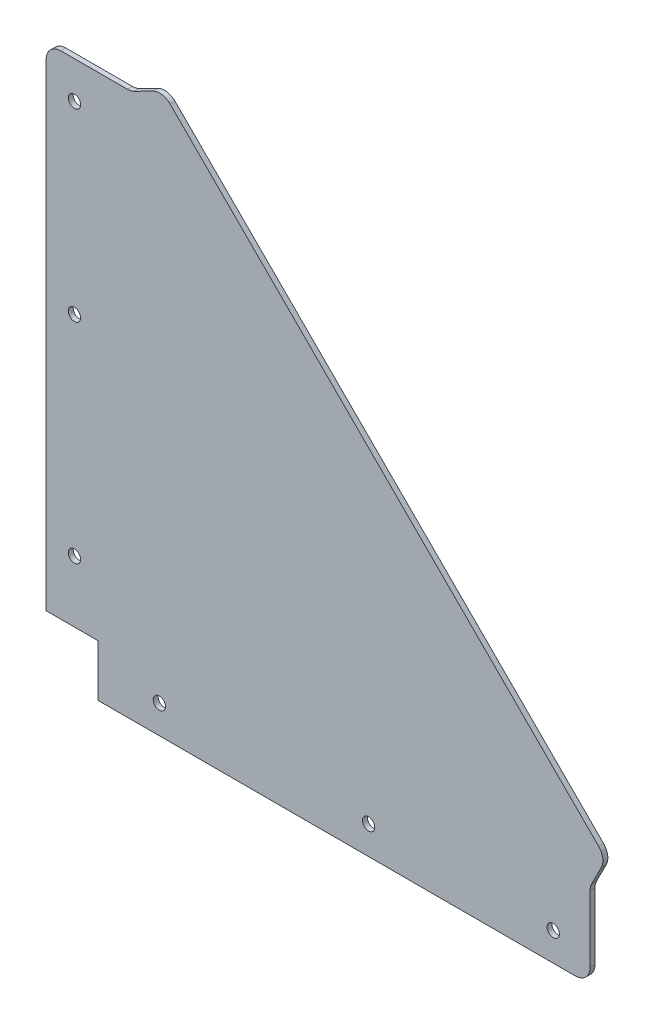
SolidWorks part; units mm, degrees
ref_plane "前基準面" through (0, 0, 0) normal (0, 0, 1) x (1, 0, 0)
ref_plane "上基準面" through (0, 0, 0) normal (0, 1, 0) x (1, 0, 0)
ref_plane "右基準面" through (0, 0, 0) normal (1, 0, 0) x (0, 0, -1)
ref_plane "平面1"
sketch "草圖1" plane through (0, 0, 0) normal (0, 0, 1) x (1, 0, 0)
  line L0 (21, 21) -> (0, 21)
  line L1 (0, 21) -> (0, 221)
  line L2 (0, 221) -> (34.5, 221)
  line L3 (34.5, 221) -> (47.3011, 227.5225)
  line L4 (47.3011, 227.5225) -> (227.5225, 47.3011)
  line L5 (227.5225, 47.3011) -> (222.5286, 37.5)
  line L6 (222.5286, 37.5) -> (221, 34.5)
  line L7 (221, 34.5) -> (221, 21)
  line L8 (221, 21) -> (221, 0)
  line L9 (221, 0) -> (21, 0)
  line L10 (21, 0) -> (21, 21)
  circle A0 centre (206, 11.5) radius 2.5
  circle A1 centre (131, 11.5) radius 2.5
  circle A2 centre (46, 11.5) radius 2.5
  circle A3 centre (11.5, 206) radius 2.5
  circle A4 centre (11.5, 131) radius 2.5
  circle A5 centre (11.5, 46) radius 2.5
  dimension "D12" = 5
  dimension "D14" = 5
  dimension "D15" = 5
  dimension "D21" = 5
  dimension "D22" = 5
  dimension "D23" = 5
  dimension "D1" = 21
  dimension "D2" = 21
  dimension "D3" = 200
  dimension "D4" = 200
  dimension "D5" = 21
  dimension "D6" = 13.5
  dimension "D7" = 153
  dimension "D8" = 16.5707
  dimension "D9" = 11
  dimension "D10" = 45
  dimension "D11" = 153
  dimension "D13" = 11.5
  dimension "D16" = 206
  dimension "D17" = 11.5
  dimension "D18" = 15
  dimension "D19" = 75
  dimension "D20" = 85
  dimension "D24" = 11.5
  dimension "D25" = 11.5
  dimension "D26" = 11.5
  dimension "D27" = 90
  dimension "D28" = 75
  dimension "D29" = 85
extrude "擠出1" add sketch "草圖1" along normal blind 2 contours L10 L9 L8 L7 L6 L5 L4 L3 L2 L1 L0 A5 A4 A3 A2 A1 A0
fillet "圓角1" radius 6 6 edges at (34.5, 221, 1) (221, 34.5, 1) (221, 0, 1) (227.5225, 47.3011, 1) (47.3011, 227.5225, 1) (0, 221, 1)
